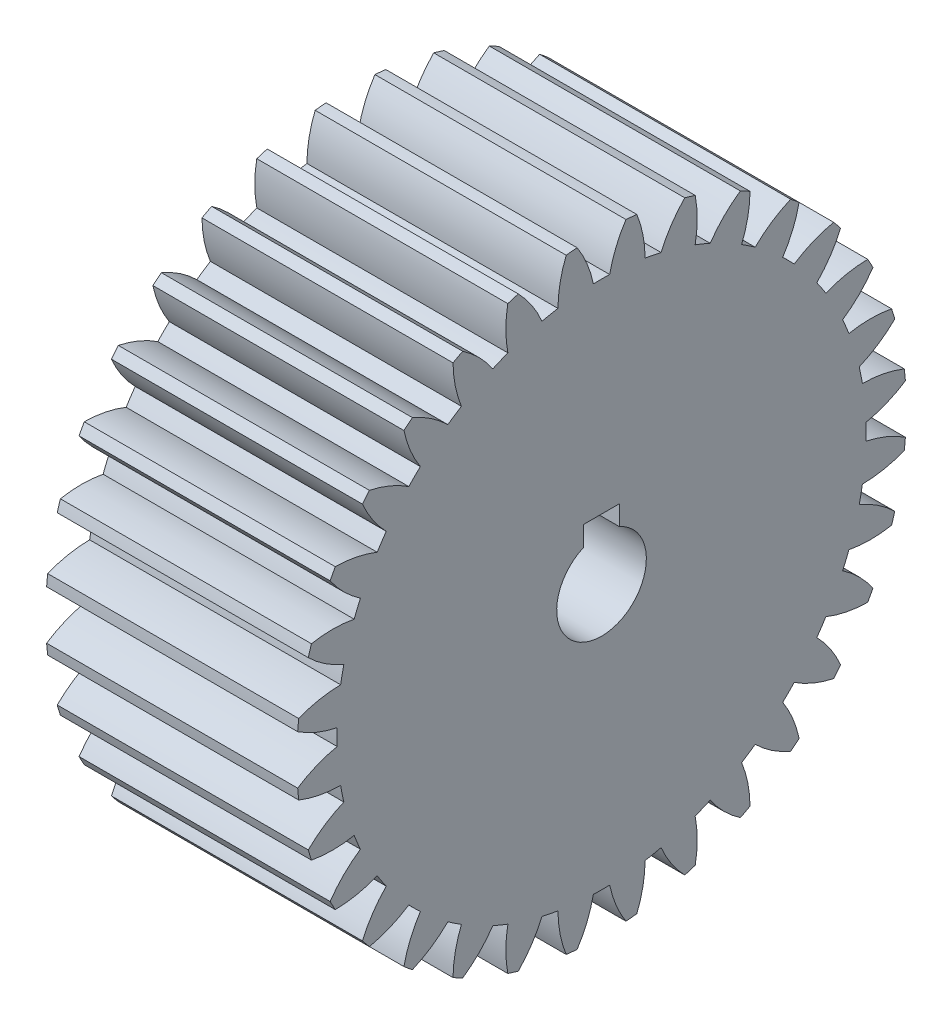
SolidWorks part; units mm, degrees
ref_plane "Plane1" through (0, 0, 0) normal (0, 0, 1) x (1, 0, 0)
ref_plane "Plane2" through (0, 0, 0) normal (0, 1, 0) x (1, 0, 0)
ref_plane "Plane3" through (0, 0, 0) normal (1, 0, 0) x (0, 0, -1)
sketch "HoldingSke" plane through (0, 0, 0) normal (0, 1, 0) x (1, 0, 0)
  line L0 (0, 0) -> (0.424, -0.265)
  line L1 (-15, 0) -> (100, 0) construction
  line L2 (0, 0) -> (-2.1039, 2.3779)
  line L3 (0, 0) -> (-11.863, 4.5341)
  line L4 (0, 0) -> (7.3237, 4.5764)
  line L5 (0, 0) -> (-46.8476, -17.4728)
  line L6 (0, 0) -> (-23.211, -15.6605)
  line L7 (-2.1039, 2.3779) -> (8.6586, 51.2059)
  line L8 (-76.2, 54.61) -> (-74.4, 54.61)
  line L9 (-71.009, 38.7566) -> (-53.1078, 45.2721)
  line L10 (-76.2, 71.12) -> (104.1128, 71.12)
  line L11 (0, 0) -> (-28, 0)
  line L12 (-76.2, 101.6) -> (-76.133, 101.6)
  line L13 (24.9733, 27.94) -> (52.9518, 28.4284)
  line L14 (24.9733, 27.94) -> (24.9743, 27.94)
  line L15 (24.9733, 27.94) -> (100.4006, 29.5858)
  line L16 (-63.627, -2) -> (-12.827, -2)
  circle A0 centre (0, 0) radius 5
  circle A1 centre (0, 0) radius 29.499
  circle A2 centre (0, 0) radius 37.5
  circle A3 centre (0, 0) radius 5
  dimension "MHD" = 58.998
  dimension "Hub_dia" = 75
  dimension "Bore" = 10
  dimension "MBD" = 10
  dimension "Num_teeth" = 32
  dimension "Pitch" = 0.5
  dimension "Overall_len" = 50
  dimension "Show_teeth" = 32
  dimension "Thickness" = 28
  dimension "OAL" = 50.0001
  dimension "T_dim" = 1.8
  dimension "Ap" = 20
  dimension "H" = 19.05
  dimension "Pitch_radius" = 180.3128
  dimension "Width" = 28
  dimension "Backlash" = 0.067
  dimension "Addendum_fac" = 1
  dimension "Dedendum_fac" = 1.25
  dimension "Clearance_fac" = 0.25
  dimension "Dedendum_add" = 0.001
  dimension "Module" = 2
sketch "BasProSke" plane through (0, 0, 0) normal (0, 1, 0) x (1, 0, 0)
  line L0 (-10, 0) -> (60, 0) construction
  line L1 (0, 0) -> (0, 34)
  line L2 (0, 0) -> (28, 0)
  line L3 (28, 0) -> (28, 34)
  line L4 (28, 34) -> (0, 34)
  dimension "Thickness" = 28
  dimension "Diameter" = 68
revolve "Base-Revolve" add sketch "BasProSke" angle 360 about L0
sketch "TooCutSke" plane through (0, 0, 0) normal (1, 0, 0) x (0, 0, -1)
  line L1 (0, 0) -> (0, 107) construction
  line L2 (0, 0) -> (-1.6874, 31.9555) construction
  line L3 (0, 0) -> (-6.2666, 63.6261) construction
  line L4 (-1.6874, 31.9555) -> (-3.1333, 31.8131) construction
  arc A0 (0.9098, 29.485) -> (-0.9098, 29.485) centre (0, 0) ccw
  arc A1 (2.7408, 33.9148) -> (-2.7408, 33.9148) centre (0, 0) ccw
  circle A2 centre (0, 0) radius 32 construction
  circle A3 centre (0, 0) radius 30.0702 construction
  arc A4 (-0.9098, 29.485) -> (-2.7408, 33.9148) centre (-13.4454, 26.8968) ccw
  arc A5 (2.7408, 33.9148) -> (0.9098, 29.485) centre (13.4454, 26.8968) ccw
  dimension "Root_dia" = 58.998
  dimension "Overcut_dia" = 68.0508
  dimension "Pitch_dia" = 64
  dimension "Base_dia" = 60.1403
  dimension "Flank_rad" = 12.8
  dimension "Half_ang" = 5.625
  dimension "Half_CT" = 1.4529
extrude "ToothCut" cut sketch "TooCutSke" along normal through all
fillet "Breaks" [suppressed] radius 0.04
fillet "RootFillets" [suppressed] radius 0.501
pattern_circular "TeethCuts" count 32 every 11.25 about axis through (-10, 0, 0) along (1, 0, 0) of "ToothCut", "RootFillets", "Breaks"
sketch "HubNeaOneSke" plane through (0, 0, 0) normal (-1, 0, 0) x (0, 0, 1)
  circle A0 centre (0, 0) radius 29.499
  dimension "Diameter" = 58.998
extrude "HubNearOne" [suppressed] add sketch "HubNeaOneSke" along normal blind 22.0001
sketch "HubNeaBotSke" plane through (0, 0, 0) normal (-1, 0, 0) x (0, 0, 1)
  circle A0 centre (0, 0) radius 29.499
  dimension "Diameter" = 58.998
extrude "HubNearBoth" [suppressed] add sketch "HubNeaBotSke" along normal blind 11
ref_plane "FarPln" through (28, 0, 0) normal (1, 0, 0) x (0, 0, -1)
sketch "HubFarSke" plane through (28, 0, 0) normal (1, 0, 0) x (0, 0, -1)
  circle A0 centre (0, 0) radius 29.499
  dimension "Diameter" = 58.998
extrude "HubFar" [suppressed] add sketch "HubFarSke" along normal blind 11
sketch "BorSke" plane through (0, 0, 0) normal (1, 0, 0) x (0, 0, -1)
  circle A0 centre (0, 0) radius 5
  dimension "Diameter" = 10
extrude "Bore" cut sketch "BorSke" along normal mid plane 100.0001
sketch "KeySke" plane through (0, 0, 0) normal (1, 0, 0) x (0, 0, -1)
  line L0 (-2, 0) -> (-2, 6.8)
  line L1 (-2, 6.8) -> (2, 6.8)
  line L2 (2, 6.8) -> (2, 0)
  line L3 (0, 0) -> (0, 34) construction
  line L4 (-2, 0) -> (2, 0)
  dimension "Offset" = 6.8
  dimension "Width" = 4
extrude "Keyway" cut sketch "KeySke" along normal mid plane 100.0001
pattern_circular "Keyway2" [suppressed] count 2 every 90 about axis through (-10, 0, 0) along (1, 0, 0)
equation "' \"Module@HoldingSke\" = 6.35"
equation "' \"Num_teeth@HoldingSke\" = 12"
equation "' \"Ap@HoldingSke\" =  20"
equation "' \"Ap@HoldingSke\" = 20"
equation "' \"Width@HoldingSke\" = 0.5 * 25.4"
equation "' \"Hub_dia@HoldingSke\"= 1 * 25.4"
equation "' \"Hub_dia@HoldingSke\" = 1 * 25.4"
equation "' \"Overall_len@HoldingSke\" = 1.0 * 25.4"
equation "' \"Bore@HoldingSke\" = 0.75 * 25.4"
equation "' \"T_dim@HoldingSke\" = 0.1 * 25.4"
equation "' \"Width@KeySke\" = 0.25 * 25.4"
equation "' \"Show_teeth@HoldingSke\" = 13"
equation "' \"Backlash@HoldingSke\" = 0.009 * 25.4"
equation "' \"Addendum_fac@HoldingSke\" = 1.0"
equation "' \"Dedendum_fac@HoldingSke\" = 1.25"
equation "' \"Dedendum_add@HoldingSke\" = 0.00005 * 25.4"
equation "' \"Clearance_fac@HoldingSke\" = 0.25"
equation "\"Pitch@HoldingSke\" = 1 / \"Module@HoldingSke\""
equation "\"Overcut_dia@TooCutSke\" = (\"Num_teeth@HoldingSke\" + 2 * \"Addendum_fac@HoldingSke\") / \"Pitch@HoldingSke\" + 0.002 * 25.4"
equation "\"Pitch_dia@TooCutSke\" = \"Num_teeth@HoldingSke\" / \"Pitch@HoldingSke\""
equation "\"Base_dia@TooCutSke\" = \"Num_teeth@HoldingSke\" / \"Pitch@HoldingSke\" * cos((\"Ap@HoldingSke\"  * 3.14159265 / 180))"
equation "\"Root_dia@TooCutSke\" = (\"Num_teeth@HoldingSke\" + 2) / \"Pitch@HoldingSke\" - 2 * (\"Addendum_fac@HoldingSke\" + \"Dedendum_fac@HoldingSke\") / \"Pitch@HoldingSke\" - \"Dedendum_add@HoldingSke\" * 2"
equation "\"Half_ang@TooCutSke\" = 180 / \"Num_teeth@HoldingSke\""
equation "\"Half_CT@TooCutSke\" = \"Num_teeth@HoldingSke\" / \"Pitch@HoldingSke\" * sin((3.14159265 / 2 / \"Num_teeth@HoldingSke\")) / 2 - 7 * \"Backlash@HoldingSke\" / 4"
equation "\"Flank_rad@TooCutSke\" = \"Num_teeth@HoldingSke\" / \"Pitch@HoldingSke\" / 5"
equation "\"Radius@RootFillets\" = \"Clearance_fac@HoldingSke\" / \"Pitch@HoldingSke\" + \"Dedendum_add@HoldingSke\""
equation "\"Break_rad@Breaks\" = 0.02 / \"Pitch@HoldingSke\""
equation "\"Thickness@HoldingSke\" = \"Width@HoldingSke\""
equation "\"OAL@HoldingSke\" = \"Thickness@HoldingSke\""
equation "\"MHD@HoldingSke\" = (\"Num_teeth@HoldingSke\" + 2) / \"Pitch@HoldingSke\" - 2 * (\"Addendum_fac@HoldingSke\" + \"Dedendum_fac@HoldingSke\")  / \"Pitch@HoldingSke\" - \"Dedendum_add@HoldingSke\" * 2"
equation "\"MBD@HoldingSke\" = (\"Num_teeth@HoldingSke\" + 2) / \"Pitch@HoldingSke\" - 2 * (\"Addendum_fac@HoldingSke\" + \"Dedendum_fac@HoldingSke\")  / \"Pitch@HoldingSke\" - \"Dedendum_add@HoldingSke\" * 2 - 0.002 * 25.4"
equation "\"MHD@HoldingSke\" = ((sgn( \"MHD@HoldingSke\" - \"Hub_dia@HoldingSke\" )-1)*( \"MHD@HoldingSke\" - \"Hub_dia@HoldingSke\" ))/-2+ \"Hub_dia@HoldingSke\""
equation "\"MBD@HoldingSke\" = ((sgn( \"MBD@HoldingSke\" - \"Bore@HoldingSke\" )-1)*( \"MBD@HoldingSke\" - \"Bore@HoldingSke\" ))/-2+ \"Bore@HoldingSke\""
equation "\"OAL@HoldingSke\" = ((sgn( \"OAL@HoldingSke\" - \"Overall_len@HoldingSke\" )+1)*( \"OAL@HoldingSke\" - \"Overall_len@HoldingSke\" ))/2 + \"Overall_len@HoldingSke\" + 0.000002 * 25.4"
equation "\"Num_teeth@TeethCuts\" = int( \"Show_teeth@HoldingSke\" ) + 1"
equation "\"Num_teeth@TeethCuts\" = ((sgn( \"Num_teeth@TeethCuts\" - \"Num_teeth@HoldingSke\" )-1)*( \"Num_teeth@TeethCuts\" - \"Num_teeth@HoldingSke\" ))/-2+ \"Num_teeth@HoldingSke\""
equation "\"Num_teeth@TeethCuts\" = ((sgn( \"Num_teeth@TeethCuts\" - 2.0)+1)*( \"Num_teeth@TeethCuts\" - 2.0))/2 +2.0"
equation "\"Angle@TeethCuts\" = 360.0 / \"Num_teeth@HoldingSke\""
equation "\"Diameter@BasProSke\" = (\"Num_teeth@HoldingSke\" + 2 * \"Addendum_fac@HoldingSke\") / \"Pitch@HoldingSke\""
equation "\"Thickness@BasProSke\"  = \"Thickness@HoldingSke\""
equation "' \"Fillet_rad@BasProSke\" =  \"Thickness@HoldingSke\" * 0.05"
equation "' \"Fillet_rad@BasProSke\" = \"Thickness@HoldingSke\" * 0.05"
equation "\"MHD@HoldingSke\" = ((sgn( \"MHD@HoldingSke\" - \"Root_dia@TooCutSke\" )-1)*( \"MHD@HoldingSke\" - \"Root_dia@TooCutSke\" ))/-2+ \"Root_dia@TooCutSke\""
equation "\"Diameter@HubNeaOneSke\" = \"MHD@HoldingSke\""
equation "\"Length@HubNearOne\" = \"OAL@HoldingSke\" - \"Thickness@BasProSke\""
equation "\"Diameter@HubNeaBotSke\" = \"MHD@HoldingSke\""
equation "\"Length@HubNearBoth\" = ( \"OAL@HoldingSke\" - \"Thickness@BasProSke\" ) / 2.0"
equation "\"Thickness@FarPln\" = \"Thickness@BasProSke\""
equation "\"Diameter@HubFarSke\" = \"MHD@HoldingSke\""
equation "\"Length@HubFar\" = ( \"OAL@HoldingSke\" - \"Thickness@BasProSke\" ) / 2.0"
equation "\"Diameter@BorSke\" = \"MBD@HoldingSke\""
equation "\"D1@Bore\" = \"OAL@HoldingSke\" * 2.0"
equation "\"D1@Keyway\" = \"OAL@HoldingSke\" * 2.0"
equation "\"Offset@KeySke\" = \"T_dim@HoldingSke\" + \"MBD@HoldingSke\" / 2.0"
